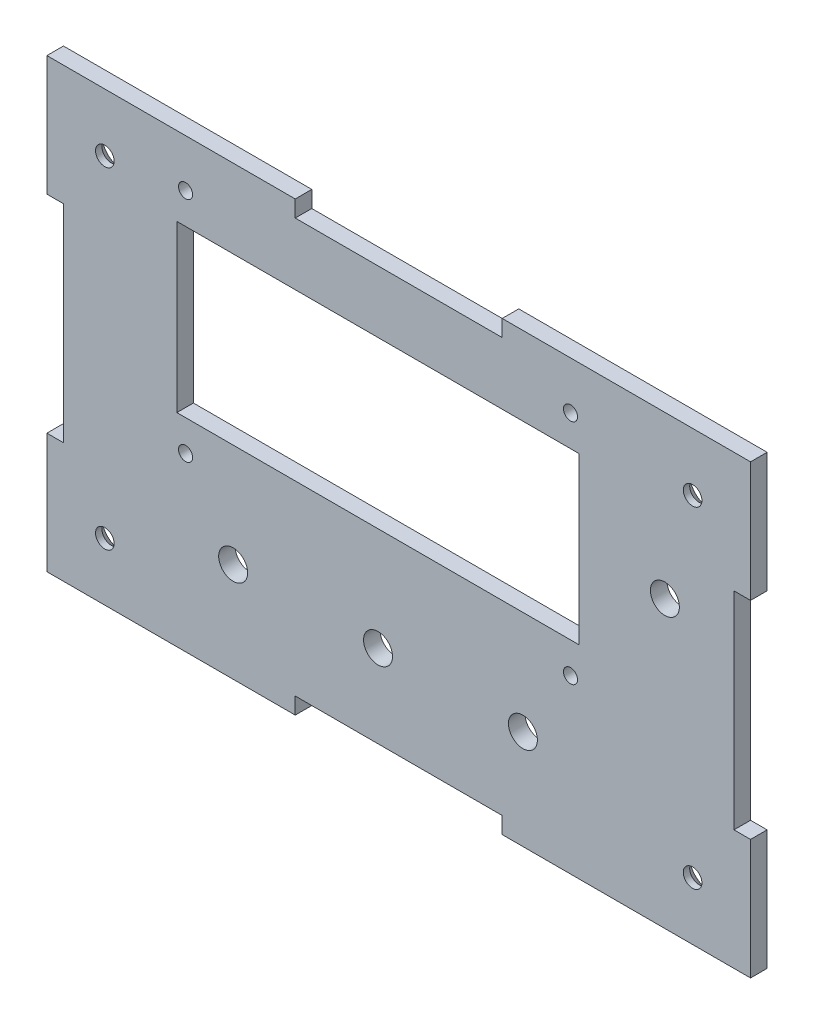
SolidWorks part; units mm, degrees
ref_plane "Front Plane" through (0, 0, 0) normal (0, 0, 1) x (1, 0, 0)
ref_plane "Top Plane" through (0, 0, 0) normal (0, 1, 0) x (1, 0, 0)
ref_plane "Right Plane" through (0, 0, 0) normal (1, 0, 0) x (0, 0, -1)
sketch "Sketch1" plane through (0, 0, 0) normal (0, 0, 1) x (1, 0, 0)
  line L1 (-85, -54) -> (85, -54)
  line L2 (-85, -54) -> (-85, 54)
  line L3 (-85, 54) -> (85, 54)
  line L4 (85, -54) -> (85, 54)
  line L5 (-85, -54) -> (85, 54) construction
  line L6 (-85, 54) -> (85, -54) construction
  point P0 (0, 0)
  dimension "D1" = 170
  dimension "D2" = 108
extrude "Plate" add sketch "Sketch1" along normal blind 4
sketch "Sketch2" plane through (0, 0, 0) normal (0, 0, -1) x (-1, 0, 0)
  line L1 (-43.6, -5) -> (53.6, -5)
  line L2 (-43.6, -5) -> (-43.6, 35)
  line L3 (-43.6, 35) -> (53.6, 35)
  line L4 (53.6, -5) -> (53.6, 35)
  line L5 (-43.6, -5) -> (53.6, 35) construction
  line L6 (-43.6, 35) -> (53.6, -5) construction
  point P0 (5, 15)
  dimension "D1" = 97.2
  dimension "D2" = 40
  dimension "D3" = 5
  dimension "D4" = 15
extrude "Screen slot" cut sketch "Sketch2" against normal through all
sketch "Screen screw hole position" plane through (0, 0, 0) normal (0, 0, -1) x (-1, 0, 0)
  line L0 (53.6, -5) -> (53.6, 35) construction
  line L1 (-43.6, -5) -> (53.6, -5) construction
  line L2 (-43.6, 35) -> (-43.6, -5) construction
  line L3 (53.6, 35) -> (-43.6, 35) construction
  line L4 (53.6, -5) -> (53.6, 35)
  line L5 (-43.6, -5) -> (53.6, -5)
  line L6 (-43.6, 35) -> (-43.6, -5)
  line L7 (53.6, 35) -> (-43.6, 35)
  line L8 (-43.6, 35) -> (53.6, -5) construction
  line L10 (-41.5, -12.5) -> (51.5, -12.5)
  line L11 (-41.5, -12.5) -> (-41.5, 42.5)
  line L12 (-41.5, 42.5) -> (51.5, 42.5)
  line L13 (51.5, -12.5) -> (51.5, 42.5)
  line L14 (-41.5, -12.5) -> (51.5, 42.5) construction
  line L15 (-41.5, 42.5) -> (51.5, -12.5) construction
  point P3 (5, 15)
  dimension "D1" = 93
  dimension "D2" = 55
hole_wizard "Screen screw holes" positions "3DSketch1" profile "Sketch5" countersink size "M3" standard "ISO" end condition up to next
sketch3d "3DSketch1"
  point P0 (41.5, 42.5, 0)
  point P3 (-51.5, 42.5, 0)
  point P6 (-51.5, -12.5, 0)
  point P9 (41.5, -12.5, 0)
sketch "Sketch5" plane through (41.5, 42.5, 0) normal (1, 0, 0) x (0, 1, 0)
  line L0 (0, 0) -> (0, 4)
  line L1 (0, 4) -> (1.7, 4)
  line L2 (1.7, 4) -> (1.7, 1.45)
  line L3 (1.7, 1.45) -> (3.15, 0)
  line L5 (3.15, 0) -> (0, 0)
  line L6 (-1.7, 1.45) -> (-3.15, 0) construction
  line L11 (0, -6.35) -> (0, 107.95) construction
  dimension "Thru Hole Dia." = 3.4
  dimension "Thru Hole Depth" = 4
  dimension "Near C'Sink Dia." = 6.3
  dimension "Near C'Sink Angle" = 90
sketch "Sketch6" plane through (0, 0, 0) normal (0, 0, -1) x (-1, 0, 0)
  line L0 (-85, -54) -> (-85, 54) construction
  line L1 (-43.6, 35) -> (-85, 35)
  line L2 (-43.6, 35) -> (-43.6, -5)
  line L3 (-43.6, -5) -> (-85, -5)
  line L4 (-85, 35) -> (-85, -5)
  line L5 (-85, 35) -> (-43.6, -5) construction
  line L6 (5, -5) -> (5, -30)
  line L7 (-43.6, -5) -> (53.6, -5) construction
  line L8 (5, -30) -> (40, -30)
  line L9 (5, -30) -> (-30, -30)
  point P7 (-64.3, 15)
  dimension "D1" = 25
  dimension "D2" = 35
hole_wizard "Knob holes" positions "3DSketch2" profile "Sketch7" hole size "Ø6.0" standard "ISO" end condition up to next
sketch3d "3DSketch2"
  point P0 (30, -30, 0)
  point P3 (-5, -30, 0)
  point P6 (-40, -30, 0)
  point P9 (64.3, 15, 0)
sketch "Sketch7" plane through (30, -30, 0) normal (1, 0, 0) x (0, 1, 0)
  line L0 (0, 0) -> (0, 4)
  line L1 (0, 4) -> (3.5, 4)
  line L2 (3.5, 4) -> (3.5, 0)
  line L5 (3.5, 0) -> (0, 0)
  line L11 (0, -6.35) -> (0, 107.95) construction
  dimension "Thru Hole Dia." = 7
  dimension "Thru Hole Depth" = 4
sketch "Sketch8" plane through (0, 0, 0) normal (0, 0, -1) x (-1, 0, 0)
  line L0 (-85, 54) -> (85, 54) construction
  line L1 (-25, 54) -> (25, 54)
  line L2 (-25, 54) -> (-25, 50)
  line L3 (-25, 50) -> (25, 50)
  line L4 (25, 54) -> (25, 50)
  line L5 (-85, 54) -> (-25, 54)
  line L6 (25, 54) -> (85, 54)
  line L7 (-85, -54) -> (-85, 54) construction
  line L8 (-85, 25) -> (-81, 25)
  line L9 (-85, 25) -> (-85, -25)
  line L10 (-85, -25) -> (-81, -25)
  line L11 (-81, 25) -> (-81, -25)
  line L12 (-85, 25) -> (-85, 54)
  line L13 (-85, -25) -> (-85, -54)
  line L14 (0, 2.2) -> (0, -2.2) construction
  line L15 (85, -25) -> (81, -25)
  line L16 (81, 25) -> (81, -25)
  line L17 (85, 25) -> (81, 25)
  line L18 (85, 25) -> (85, -25)
  line L19 (2.2, 0) -> (-2.2, 0) construction
  line L20 (-25, -50) -> (25, -50)
  line L21 (25, -54) -> (25, -50)
  line L22 (-25, -54) -> (25, -54)
  line L23 (-25, -54) -> (-25, -50)
  line M25 (-85, 54) -> (-85, -54)
  line M26 (-85, -54) -> (85, -54)
  line M27 (85, -54) -> (85, 54)
  line M28 (85, 54) -> (-85, 54)
  dimension "D1" = 50
  dimension "D2" = 4
  dimension "D3" = 50
  dimension "D4" = 4
extrude "Cut-Extrude2" cut sketch "Sketch8" against normal up to next contours L4 L2 L3 M28 | L17 L16 L15 M27 | L23 L21 L20 M26 | L11 L8 L10 M25
sketch "Sketch9" plane through (0, 0, 0) normal (0, 0, -1) x (-1, 0, 0)
  line L0 (81, 25) -> (81, -25) construction
  line L1 (-71, 40) -> (71, 40)
  line L2 (-71, 40) -> (-71, -40)
  line L3 (-71, -40) -> (71, -40)
  line L4 (71, 40) -> (71, -40)
  line L5 (-25, 50) -> (25, 50) construction
  line L6 (-25, -50) -> (25, -50) construction
  line L7 (-81, 25) -> (-81, -25) construction
  dimension "D1" = 10
  dimension "D2" = 10
  dimension "D3" = 10
  dimension "D4" = 10
hole_wizard "CSK for M4 Countersunk Flat Head Screw1" positions "3DSketch3" profile "Sketch10" countersink size "M4" standard "ISO" end condition up to next
sketch3d "3DSketch3"
  point P0 (71, 40, 0)
  point P3 (-71, 40, 0)
  point P6 (-71, -40, 0)
  point P9 (71, -40, 0)
sketch "Sketch10" plane through (71, 40, 0) normal (1, 0, 0) x (0, 1, 0)
  line L0 (0, 0) -> (0, 4)
  line L1 (0, 4) -> (2.25, 4)
  line L2 (2.25, 4) -> (2.25, 2.45)
  line L3 (2.25, 2.45) -> (4.7, 0)
  line L5 (4.7, 0) -> (0, 0)
  line L6 (-2.25, 2.45) -> (-4.7, 0) construction
  line L11 (0, -6.35) -> (0, 107.95) construction
  dimension "Thru Hole Dia." = 4.5
  dimension "Thru Hole Depth" = 4
  dimension "Near C'Sink Dia." = 9.4
  dimension "Near C'Sink Angle" = 90
